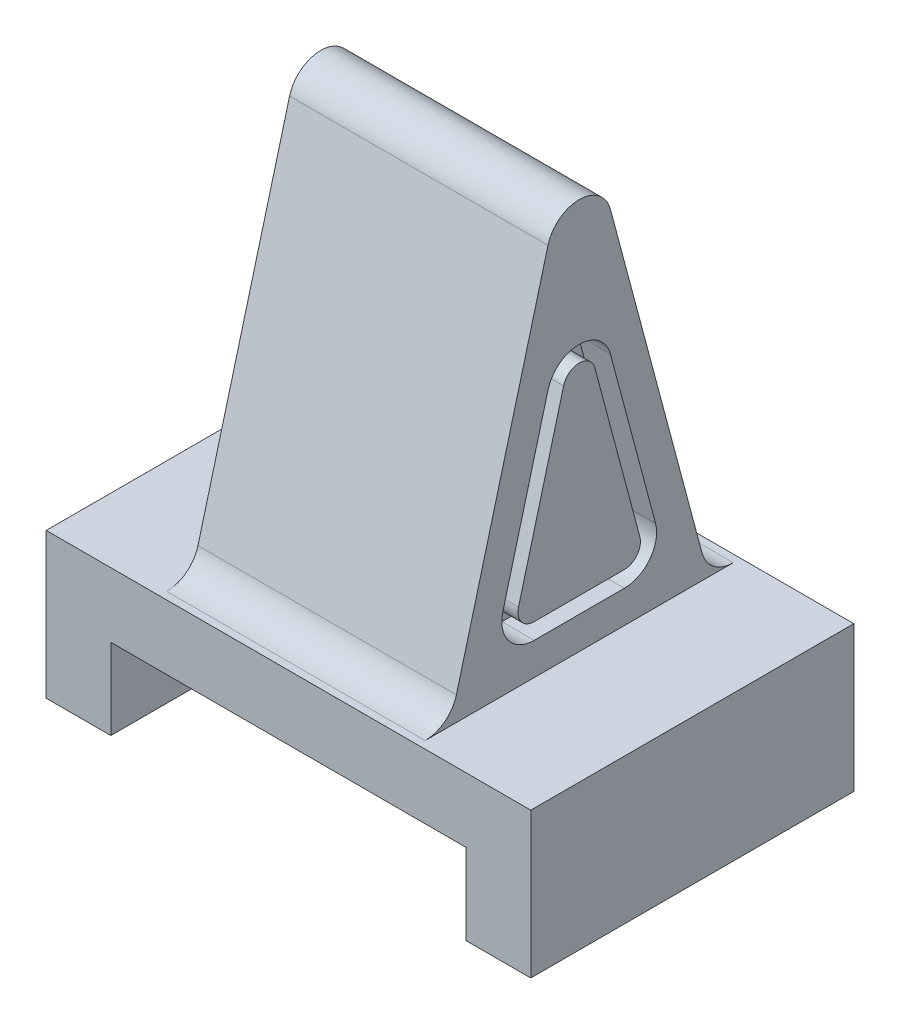
SolidWorks part; units mm, degrees
ref_plane "前视基准面" through (0, 0, 0) normal (0, 0, 1) x (1, 0, 0)
ref_plane "上视基准面" through (0, 0, 0) normal (0, 1, 0) x (1, 0, 0)
ref_plane "右视基准面" through (0, 0, 0) normal (1, 0, 0) x (0, 0, -1)
other "Configuration Table"
sketch "草图1" plane through (0, 0, 0) normal (0, 0, 1) x (1, 0, 0)
  line L0 (0, 0) -> (0, 2.5)
  line L1 (0, 2.5) -> (11, 2.5)
  line L2 (11, 2.5) -> (11, 0)
  line L3 (0, 0) -> (-2, 0)
  line L4 (-2, 0) -> (-2, 4.5)
  line L5 (-2, 4.5) -> (13, 4.5)
  line L6 (13, 4.5) -> (13, 0)
  line L7 (13, 0) -> (11, 0)
  dimension "D1" = 11
  dimension "D2" = 2.5
  dimension "D3" = 2
  dimension "D4" = 2
  dimension "D5" = 2
extrude "凸台-拉伸1" add sketch "草图1" along normal blind 10
ref_plane "基准面1" through (0, 0, 5) normal (0, 0, 1) x (1, 0, 0)
ref_plane "基准面2" through (5.5, 0, 0) normal (1, 0, 0) x (0, 0, -1)
sketch "草图7" plane through (5.5, 0, 0) normal (1, 0, 0) x (0, 0, -1)
  line L0 (-9, 4.5) -> (-5, 19.5)
  line L1 (-10, 4.5) -> (0, 4.5) construction
  line L2 (-5, 19.5) -> (-1, 4.5)
  line L3 (-1, 4.5) -> (-9, 4.5)
  line L4 (-5, 4.5) -> (-5, 19.5) construction
  point P6 (-5, 4.5)
  dimension "D1" = 8
  dimension "D2" = 15
extrude "凸台-拉伸3" add sketch "草图7" along normal blind 4 and the other way blind 4
fillet "圆角3" radius 1 3 edges at (5.5, 4.5, 1) (5.5, 4.5, 9) (5.5, 19.5, 5)
sketch "草图8" plane through (9.5, 0, 0) normal (1, 0, 0) x (0, 0, -1)
  line L0 (-5.9662, 11.9956) -> (-7.363, 6.7577)
  line L1 (-6.3968, 5.5) -> (-3.6032, 5.5)
  line L2 (-2.637, 6.7577) -> (-4.0338, 11.9956)
  line L3 (-1.198, 5.2423) -> (-4.0338, 15.8766)
  line L4 (-5.9662, 15.8766) -> (-8.802, 5.2423)
  line L5 (-9.7683, 4.5) -> (-0.2317, 4.5)
  line L6 (-1.198, 5.2423) -> (-4.0338, 15.8766)
  line L7 (-5.9662, 15.8766) -> (-8.802, 5.2423)
  line L8 (-9.7683, 4.5) -> (-0.2317, 4.5)
  line L9 (-7.6984, 5.5) -> (-2.3016, 5.5) construction
  line L10 (-2.3016, 5.5) -> (-5, 15.619) construction
  line L11 (-5, 15.619) -> (-7.6984, 5.5) construction
  line L12 (-3.1201, 6.6288) -> (-4.5169, 11.8667)
  line L13 (-5.4831, 11.8667) -> (-6.8799, 6.6288)
  line L14 (-6.3968, 6) -> (-3.6032, 6)
  arc A3 (-4.0338, 15.8766) -> (-5.9662, 15.8766) centre (-5, 15.619) ccw
  arc A4 (-9.7683, 4.5) -> (-8.802, 5.2423) centre (-9.7683, 5.5) ccw
  arc A5 (-1.198, 5.2423) -> (-0.2317, 4.5) centre (-0.2317, 5.5) ccw
  arc A6 (-4.0338, 15.8766) -> (-5.9662, 15.8766) centre (-5, 15.619) ccw
  arc A7 (-9.7683, 4.5) -> (-8.802, 5.2423) centre (-9.7683, 5.5) ccw
  arc A8 (-1.198, 5.2423) -> (-0.2317, 4.5) centre (-0.2317, 5.5) ccw
  arc A9 (-3.6032, 5.5) -> (-2.637, 6.7577) centre (-3.6032, 6.5) ccw
  arc A10 (-2.3016, 5.5) -> (-2.3016, 5.5) centre (-2.3016, 5.5) cw construction
  arc A11 (-7.363, 6.7577) -> (-6.3968, 5.5) centre (-6.3968, 6.5) ccw
  arc A12 (-7.6984, 5.5) -> (-7.6984, 5.5) centre (-7.6984, 5.5) cw construction
  arc A13 (-4.0338, 11.9956) -> (-5.9662, 11.9956) centre (-5, 11.7379) ccw
  arc A14 (-5, 15.619) -> (-5, 15.619) centre (-5, 15.619) ccw construction
  arc A15 (-3.6032, 6) -> (-3.1201, 6.6288) centre (-3.6032, 6.5) ccw
  arc A16 (-4.5169, 11.8667) -> (-5.4831, 11.8667) centre (-5, 11.7379) ccw
  arc A17 (-6.8799, 6.6288) -> (-6.3968, 6) centre (-6.3968, 6.5) ccw
  dimension "D3" = 1
  dimension "D1" = 0
  dimension "D2" = 1
  dimension "D4" = 0.5
extrude "切除-拉伸2" cut sketch "草图8" against normal blind 1 contours L2 A13 L0 A11 L1 A9 A17 L13 A16 L12 A15 L14
mirror "镜向1" about plane through (5.5, 0, 0) normal (1, 0, 0) of "切除-拉伸2"
